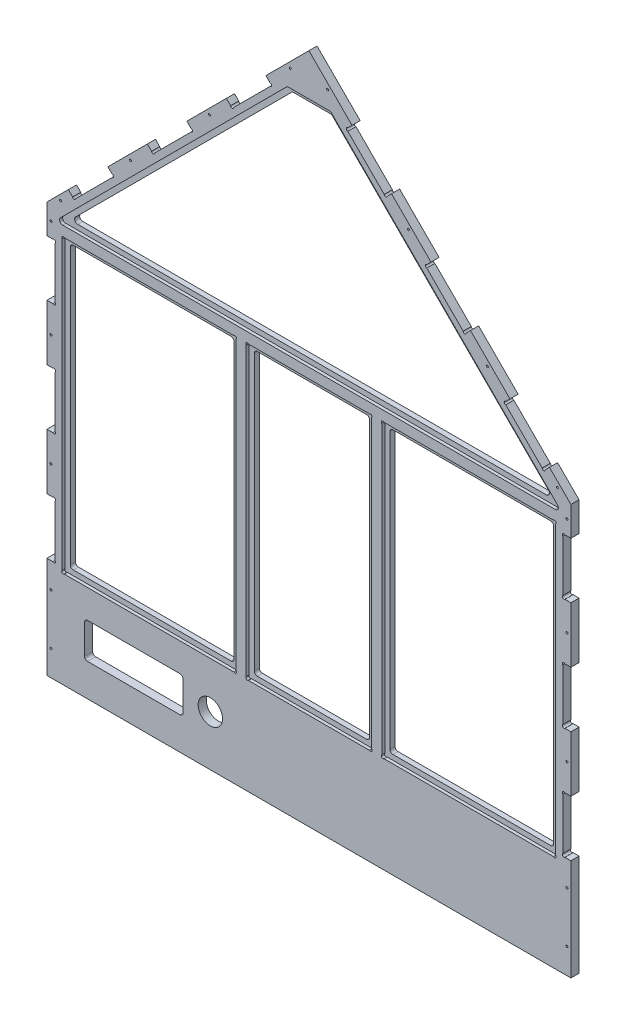
SolidWorks part; units mm, degrees
ref_plane "Plan de face" through (0, 0, 0) normal (0, 0, 1) x (1, 0, 0)
ref_plane "Plan de dessus" through (0, 0, 0) normal (0, 1, 0) x (1, 0, 0)
ref_plane "Plan de droite" through (0, 0, 0) normal (1, 0, 0) x (0, 0, -1)
sketch "Esquisse1" plane through (0, 0, 0) normal (0, 0, 1) x (1, 0, 0)
  line L0 (-49.8943, -43.7861) -> (466.1057, -43.7861)
  line L1 (-49.8943, -43.7861) -> (-49.8943, 56.2139)
  line L2 (-49.8943, 56.2139) -> (-44.0156, 56.2139)
  line L3 (-41.8943, 58.3352) -> (-41.8943, 109.0925)
  line L4 (-44.0156, 111.2139) -> (-49.8943, 111.2139)
  line L5 (-49.8943, 111.2139) -> (-49.8943, 166.2139)
  line L6 (-49.8943, 166.2139) -> (-44.0156, 166.2139)
  line L7 (-41.8943, 168.3352) -> (-41.8943, 219.0925)
  line L8 (-44.0156, 221.2139) -> (-49.8943, 221.2139)
  line L9 (-49.8943, 221.2139) -> (-49.8943, 276.2139)
  line L10 (-49.8943, 276.2139) -> (-44.0156, 276.2139)
  line L11 (-41.8943, -43.7861) -> (-41.8943, 356.7483) construction
  line L12 (208.1057, -177.1891) -> (208.1057, 755.1727) construction
  line L13 (-41.8943, 356.7483) -> (208.1057, 606.7483) construction
  line L14 (-41.8943, 278.3352) -> (-41.8943, 329.0925)
  line L15 (-44.0156, 331.2139) -> (-49.8943, 331.2139)
  line L16 (-83.8488, 56.2139) -> (458.1057, 56.2139) construction
  line L17 (-49.8943, 331.2139) -> (-49.8943, 360.062)
  line L18 (87.8976, 497.8539) -> (92.0544, 493.697)
  line L19 (-49.8943, 360.062) -> (-28.775, 381.1813)
  line L20 (466.1057, -43.7861) -> (466.1057, 56.2139)
  line L21 (466.1057, 56.2139) -> (460.227, 56.2139)
  line L22 (458.1057, 58.3352) -> (458.1057, 109.0925)
  line L23 (466.1057, 331.2139) -> (466.1057, 360.062)
  line L24 (460.227, 331.2139) -> (466.1057, 331.2139)
  line L25 (458.1057, 278.3352) -> (458.1057, 329.0925)
  line L26 (466.1057, 276.2139) -> (460.227, 276.2139)
  line L27 (466.1057, 221.2139) -> (466.1057, 276.2139)
  line L28 (460.227, 221.2139) -> (466.1057, 221.2139)
  line L29 (458.1057, 168.3352) -> (458.1057, 219.0925)
  line L30 (466.1057, 166.2139) -> (460.227, 166.2139)
  line L31 (466.1057, 111.2139) -> (466.1057, 166.2139)
  line L32 (460.227, 111.2139) -> (466.1057, 111.2139)
  line L33 (466.1057, 360.062) -> (444.9865, 381.1813)
  line L34 (-29.8943, 56.2139) -> (-29.8943, 465.5071) construction
  line L35 (-29.8943, 353.1159) -> (188.8393, 571.8495)
  line L36 (-29.8943, 333.1159) -> (446.1057, 333.1159) construction
  line L37 (-29.8943, 56.2139) -> (-29.8943, 333.1159)
  line L38 (-29.8943, 333.1159) -> (131.3196, 333.1159)
  line L39 (131.3196, 333.1159) -> (131.3196, 56.2139)
  line L40 (131.3196, 56.2139) -> (-29.8943, 56.2139)
  line L41 (151.3196, 333.1159) -> (151.3196, 56.2139)
  line L42 (151.3196, 56.2139) -> (264.8919, 56.2139)
  line L43 (151.3196, 333.1159) -> (264.8919, 333.1159)
  line L44 (446.1057, 56.2139) -> (446.1057, 333.1159)
  line L45 (284.8919, 56.2139) -> (446.1057, 56.2139)
  line L46 (264.8919, 333.1159) -> (264.8919, 56.2139)
  line L47 (284.8919, 333.1159) -> (284.8919, 56.2139)
  line L48 (446.1057, 333.1159) -> (284.8919, 333.1159)
  line L49 (446.1057, 353.1159) -> (227.3722, 571.8495)
  line L50 (466.1057, 6.2139) -> (276.126, 6.2139) construction
  line L53 (165.6793, 575.6356) -> (169.8362, 571.4788)
  line L54 (169.8362, 568.4788) -> (133.9453, 532.5879)
  line L55 (130.9453, 532.5879) -> (126.7884, 536.7447)
  line L56 (165.6793, 575.6356) -> (208.1057, 618.062)
  line L57 (92.0544, 490.697) -> (56.1636, 454.8061)
  line L58 (53.1636, 454.8061) -> (49.0067, 458.963)
  line L59 (87.8976, 497.8539) -> (126.7884, 536.7447)
  line L60 (10.1158, 420.0721) -> (14.2727, 415.9153)
  line L61 (14.2727, 412.9153) -> (-21.6182, 377.0244)
  line L62 (-24.6182, 377.0244) -> (-28.775, 381.1813)
  line L63 (10.1158, 420.0721) -> (49.0067, 458.963)
  line L64 (440.8296, 377.0244) -> (444.9865, 381.1813)
  line L65 (188.8393, 571.8495) -> (227.3722, 571.8495)
  line L66 (401.9388, 412.9153) -> (437.8296, 377.0244)
  line L67 (406.0956, 420.0721) -> (401.9388, 415.9153)
  line L68 (363.0479, 454.8061) -> (367.2047, 458.963)
  line L69 (324.157, 490.697) -> (360.0479, 454.8061)
  line L70 (328.3139, 497.8539) -> (324.157, 493.697)
  line L71 (285.2661, 532.5879) -> (289.423, 536.7447)
  line L72 (246.3753, 568.4788) -> (282.2662, 532.5879)
  line L73 (250.5321, 575.6356) -> (246.3753, 571.4788)
  line L74 (250.5321, 575.6356) -> (208.1057, 618.062)
  line L75 (328.3139, 497.8539) -> (289.423, 536.7447)
  line L76 (406.0956, 420.0721) -> (367.2047, 458.963)
  line L77 (-58.2246, 353.1159) -> (516.6507, 353.1159) construction
  line L78 (-29.8943, 353.1159) -> (446.1057, 353.1159)
  line L85 (-49.8943, 360.062) -> (-49.8943, -43.7861) construction
  line L86 (460.227, 56.2139) -> (493.233, 56.2139) construction
  line L87 (466.1057, -43.7861) -> (458.1057, -43.7861) construction
  line L88 (458.1057, -43.7861) -> (458.1057, 345.6379) construction
  line L89 (458.1057, 345.6379) -> (466.1057, 345.6379) construction
  line L90 (462.1057, 345.6379) -> (462.1057, -43.7861) construction
  line L91 (466.1057, 138.7139) -> (462.1057, 138.7139) construction
  line L92 (466.1057, 248.7139) -> (462.1057, 248.7139) construction
  line L93 (466.1057, 6.2139) -> (471.8629, 6.2139) construction
  line L94 (471.8629, 6.2139) -> (471.8629, 56.2139) construction
  line L95 (471.8629, 56.2139) -> (466.1057, 56.2139) construction
  line L96 (471.8629, 31.2139) -> (462.1057, 31.2139) construction
  line L97 (246.3753, 579.7925) -> (240.7184, 574.1356) construction
  line L98 (240.7184, 574.1356) -> (460.227, 354.627) construction
  line L99 (460.227, 354.627) -> (466.1057, 360.062) construction
  line L100 (240.7184, 574.1356) -> (202.4489, 612.4052) construction
  line L101 (308.8684, 517.2993) -> (303.2116, 511.6425) construction
  line L102 (386.6502, 439.5176) -> (380.9933, 433.8607) construction
  line L103 (455.5461, 370.6216) -> (449.8893, 364.9648) construction
  line L104 (229.3189, 596.8488) -> (223.6621, 591.192) construction
  arc A0 (-44.0156, 56.2139) -> (-41.8943, 58.3352) centre (-42.9549, 57.2745) ccw
  arc A1 (-41.8943, 109.0925) -> (-44.0156, 111.2139) centre (-42.9549, 110.1532) ccw
  arc A2 (-44.0156, 166.2139) -> (-41.8943, 168.3352) centre (-42.9549, 167.2745) ccw
  arc A3 (-41.8943, 219.0925) -> (-44.0156, 221.2139) centre (-42.9549, 220.1532) ccw
  arc A4 (-44.0156, 276.2139) -> (-41.8943, 278.3352) centre (-42.9549, 277.2745) ccw
  arc A5 (-41.8943, 329.0925) -> (-44.0156, 331.2139) centre (-42.9549, 330.1532) ccw
  arc A6 (-24.6182, 377.0244) -> (-21.6182, 377.0244) centre (-23.1182, 377.0244) ccw
  arc A7 (14.2727, 412.9153) -> (14.2727, 415.9153) centre (14.2727, 414.4153) ccw
  arc A8 (53.1636, 454.8061) -> (56.1636, 454.8061) centre (54.6636, 454.8061) ccw
  arc A9 (92.0544, 490.697) -> (92.0544, 493.697) centre (92.0544, 492.197) ccw
  arc A10 (130.9453, 532.5879) -> (133.9453, 532.5879) centre (132.4453, 532.5879) ccw
  arc A11 (169.8362, 568.4788) -> (169.8362, 571.4788) centre (169.8362, 569.9788) ccw
  arc A12 (460.227, 56.2139) -> (458.1057, 58.3352) centre (459.1664, 57.2745) cw
  arc A13 (458.1057, 109.0925) -> (460.227, 111.2139) centre (459.1664, 110.1532) cw
  arc A14 (460.227, 166.2139) -> (458.1057, 168.3352) centre (459.1664, 167.2745) cw
  arc A15 (458.1057, 219.0925) -> (460.227, 221.2139) centre (459.1664, 220.1532) cw
  arc A16 (460.227, 276.2139) -> (458.1057, 278.3352) centre (459.1664, 277.2745) cw
  arc A17 (458.1057, 329.0925) -> (460.227, 331.2139) centre (459.1664, 330.1532) cw
  arc A18 (440.8296, 377.0244) -> (437.8296, 377.0244) centre (439.3296, 377.0244) cw
  arc A19 (401.9388, 412.9153) -> (401.9388, 415.9153) centre (401.9388, 414.4153) cw
  arc A20 (363.0479, 454.8061) -> (360.0479, 454.8061) centre (361.5479, 454.8061) cw
  arc A21 (324.157, 490.697) -> (324.157, 493.697) centre (324.157, 492.197) cw
  arc A22 (285.2661, 532.5879) -> (282.2662, 532.5879) centre (283.7662, 532.5879) cw
  arc A23 (246.3753, 568.4788) -> (246.3753, 571.4788) centre (246.3753, 569.9788) cw
  circle A24 centre (462.1057, 31.2139) radius 1
  circle A25 centre (462.1057, 138.7139) radius 1
  circle A26 centre (462.1057, 248.7139) radius 1
  circle A27 centre (462.1057, 345.6379) radius 1
  circle A28 centre (462.1057, -18.7861) radius 1
  circle A29 centre (-45.8943, 345.6379) radius 1
  circle A30 centre (-45.8943, 248.7139) radius 1
  circle A31 centre (-45.8943, 138.7139) radius 1
  circle A32 centre (-45.8943, 31.2139) radius 1
  circle A33 centre (-45.8943, -18.7861) radius 1
  circle A34 centre (226.4905, 594.0204) radius 1
  circle A35 centre (306.04, 514.4709) radius 1
  circle A36 centre (383.8218, 436.6891) radius 1
  circle A37 centre (452.7177, 367.7932) radius 1
  circle A38 centre (189.7209, 594.0204) radius 1
  circle A39 centre (110.1714, 514.4709) radius 1
  circle A40 centre (32.3897, 436.6891) radius 1
  circle A41 centre (-36.5062, 367.7932) radius 1
  point P56 (208.1057, 56.2139)
  point P57 (208.1057, 333.1159)
  point P62 (208.1057, 357.3448)
  dimension "D2" = 20
  dimension "D3" = 100
  dimension "D4" = 100
  dimension "D5" = 60
  dimension "D6" = 55
  dimension "D7" = 55
  dimension "D8" = 55
  dimension "D9" = 55
  dimension "D10" = 55
  dimension "D11" = 20
  dimension "D12" = 45
  dimension "D14" = 135
  dimension "D15" = 20
  dimension "D16" = 8
  dimension "D17" = 113.5723
  dimension "D18" = 258
  dimension "D19" = 135
  dimension "D20" = 403.8482
  dimension "D23" = 55
  dimension "D24" = 55
  dimension "D25" = 55
  dimension "D26" = 55
  dimension "D27" = 55
extrude "Boss.-Extru.1" add sketch "Esquisse1" along normal blind 8
sketch "Esquisse3" plane through (0, 0, 8) normal (0, 0, 1) x (1, 0, 0)
  line L0 (131.3196, 333.1159) -> (-29.8943, 333.1159) construction
  line L1 (-32.773, 338.1159) -> (134.1983, 338.1159)
  line L2 (-34.8943, 335.9946) -> (-34.8943, 53.3352)
  line L3 (-32.773, 51.2139) -> (134.1983, 51.2139)
  line L4 (451.1057, 335.9946) -> (451.1057, 53.3352)
  line L5 (-29.8943, 333.1159) -> (-29.8943, 56.2139) construction
  line L6 (-29.8943, 56.2139) -> (131.3196, 56.2139) construction
  line L7 (446.1057, 56.2139) -> (446.1057, 333.1159) construction
  line L8 (186.7682, 576.8495) -> (229.4432, 576.8495)
  line L9 (185.7087, 568.7189) -> (182.1732, 572.2544) construction
  line L10 (188.8393, 571.8495) -> (-29.8943, 353.1159) construction
  line L11 (208.1057, 571.8495) -> (208.1057, 576.8495) construction
  line L12 (136.3196, 53.3352) -> (136.3196, 335.9946)
  line L13 (146.3196, 335.9946) -> (146.3196, 53.3352)
  line L14 (227.3722, 571.8495) -> (188.8393, 571.8495) construction
  line L15 (279.8919, 335.9946) -> (279.8919, 53.3352)
  line L16 (186.7682, 576.8495) -> (-41.7058, 348.1159)
  line L17 (208.1057, 571.8495) -> (208.1057, 348.1159) construction
  line L18 (192.3328, 353.1159) -> (192.3328, 348.1159) construction
  line L19 (-29.8943, 353.1159) -> (446.1057, 353.1159) construction
  line L20 (457.9173, 348.1159) -> (-41.7058, 348.1159)
  line L21 (229.4432, 576.8495) -> (457.9173, 348.1159)
  line L22 (269.8919, 53.3352) -> (269.8919, 335.9946)
  line L23 (131.3196, 56.2139) -> (131.3196, 333.1159) construction
  line L24 (151.3196, 333.1159) -> (151.3196, 56.2139) construction
  line L25 (264.8919, 56.2139) -> (264.8919, 333.1159) construction
  line L26 (284.8919, 333.1159) -> (284.8919, 56.2139) construction
  line L27 (148.4409, 338.1159) -> (267.7706, 338.1159)
  line L28 (282.0132, 338.1159) -> (448.9844, 338.1159)
  line L29 (282.0132, 51.2139) -> (448.9844, 51.2139)
  line L30 (148.4409, 51.2139) -> (267.7706, 51.2139)
  arc A0 (-32.773, 338.1159) -> (-34.8943, 335.9946) centre (-33.8336, 337.0552) ccw
  arc A1 (-34.8943, 53.3352) -> (-32.773, 51.2139) centre (-33.8336, 52.2745) ccw
  arc A2 (448.9844, 338.1159) -> (451.1057, 335.9946) centre (450.0451, 337.0552) cw
  arc A3 (451.1057, 53.3352) -> (448.9844, 51.2139) centre (450.0451, 52.2745) cw
  arc A4 (136.3196, 335.9946) -> (134.1983, 338.1159) centre (135.2589, 337.0552) ccw
  arc A5 (134.1983, 51.2139) -> (136.3196, 53.3352) centre (135.2589, 52.2745) ccw
  arc A6 (146.3196, 53.3352) -> (148.4409, 51.2139) centre (147.3802, 52.2745) ccw
  arc A7 (148.4409, 338.1159) -> (146.3196, 335.9946) centre (147.3802, 337.0552) ccw
  arc A8 (269.8919, 335.9946) -> (267.7706, 338.1159) centre (268.8312, 337.0552) ccw
  arc A9 (267.7706, 51.2139) -> (269.8919, 53.3352) centre (268.8312, 52.2745) ccw
  arc A10 (282.0132, 338.1159) -> (279.8919, 335.9946) centre (280.9525, 337.0552) ccw
  arc A11 (279.8919, 53.3352) -> (282.0132, 51.2139) centre (280.9525, 52.2745) ccw
  point P31 (-41.7058, 348.1159)
  dimension "D6" = 228.7336
  dimension "D1" = 5
  dimension "D2" = 5
  dimension "D3" = 5
  dimension "D4" = 5
  dimension "D5" = 5
  dimension "D7" = 5
  dimension "D8" = 5
  dimension "D9" = 5
  dimension "D10" = 5
extrude "Enlèv. mat.-Extru.1" cut sketch "Esquisse3" against normal blind 3
sketch "Esquisse4" plane through (0, 0, 0) normal (0, 0, -1) x (-1, 0, 0)
  line L0 (-111.0181, -51.7317) -> (-111.0181, 28.8675) construction
  line L1 (12.8919, -36.3183) -> (12.8919, 28.8675) construction
  line L2 (18.561, 23.2139) -> (-99.1503, 23.2139) construction
  line L3 (17.8081, -11.7861) -> (-99.1503, -11.7861) construction
  line L4 (-84.1081, -36.3183) -> (-84.1081, 28.8675) construction
  line L5 (-151.8126, 5.7139) -> (-21.4411, 5.7139) construction
  line L6 (49.8943, 56.2139) -> (49.8943, -43.7861) construction
  line L7 (49.8943, -43.7861) -> (-466.1057, -43.7861) construction
  line L9 (9.8919, -11.7861) -> (-81.1081, -11.7861)
  line L10 (12.8919, -8.7861) -> (12.8919, 20.2139)
  line L11 (9.8919, 23.2139) -> (-81.1081, 23.2139)
  line L12 (-84.1081, -8.7861) -> (-84.1081, 20.2139)
  arc A0 (-81.1081, 23.2139) -> (-84.1081, 20.2139) centre (-81.1081, 20.2139) ccw
  arc A1 (-81.1081, -11.7861) -> (-84.1081, -8.7861) centre (-81.1081, -8.7861) cw
  arc A2 (9.8919, -11.7861) -> (12.8919, -8.7861) centre (9.8919, -8.7861) ccw
  arc A3 (12.8919, 20.2139) -> (9.8919, 23.2139) centre (9.8919, 20.2139) ccw
  circle A4 centre (-111.0181, 5.7139) radius 12
  point P23 (-84.1081, 23.2139)
  point P28 (12.8919, -11.7861)
  dimension "D1" = 160.9124
  dimension "D7" = 3
  dimension "D2" = 49.5
  dimension "D3" = 35
  dimension "D4" = 97
  dimension "D5" = 17.5
  dimension "D6" = 26.91
extrude "Enlèv. mat.-Extru.2" cut sketch "Esquisse4" against normal blind 8
fillet "Congé2" radius 3 1 edges at (-41.7058, 348.1159, 6.5)
fillet "Congé3" radius 3 1 edges at (457.9173, 348.1159, 6.5)
fillet "Congé4" radius 3 12 edges at (446.1057, 333.1159, 2.5) (284.8919, 333.1159, 2.5) (284.8919, 56.2139, 2.5) (446.1057, 56.2139, 2.5) (264.8919, 56.2139, 2.5) (264.8919, 333.1159, 2.5) (151.3196, 333.1159, 2.5) (151.3196, 56.2139, 2.5) (-29.8943, 56.2139, 2.5) (131.3196, 56.2139, 2.5) (131.3196, 333.1159, 2.5) (-29.8943, 333.1159, 2.5)
fillet "Congé5" radius 3 2 edges at (446.1057, 353.1159, 2.5) (-29.8943, 353.1159, 2.5)
fillet "Congé6" radius 3 2 edges at (188.8393, 571.8495, 2.5) (227.3722, 571.8495, 2.5)
